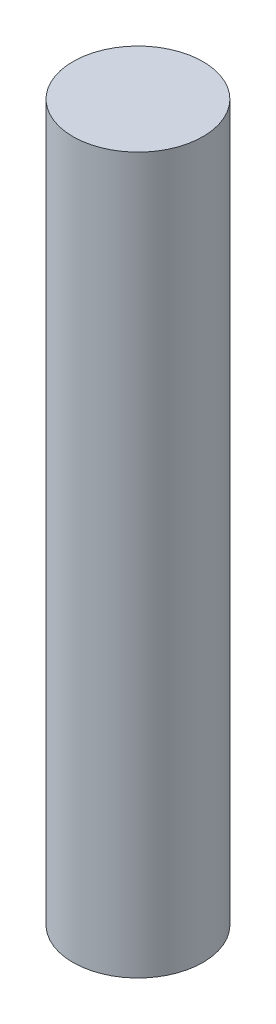
SolidWorks part; units mm, degrees
ref_plane "前视基准面" through (0, 0, 0) normal (0, 0, 1) x (1, 0, 0)
ref_plane "上视基准面" through (0, 0, 0) normal (0, 1, 0) x (1, 0, 0)
ref_plane "右视基准面" through (0, 0, 0) normal (1, 0, 0) x (0, 0, -1)
sketch "草图1" plane through (0, 0, 0) normal (0, 1, 0) x (1, 0, 0)
  circle A0 centre (0, 0) radius 2
extrude "凸台-拉伸1" add sketch "草图1" along normal blind 22
